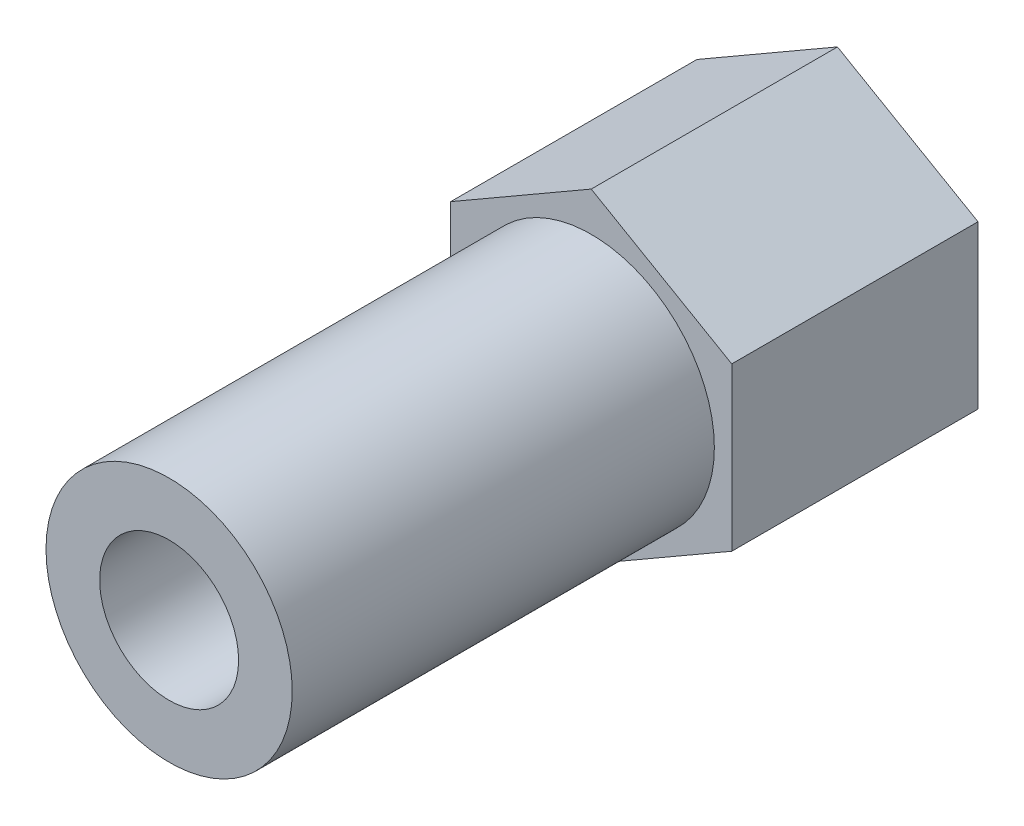
SolidWorks part; units mm, degrees
ref_plane "Plano frontal" through (0, 0, 0) normal (0, 0, 1) x (1, 0, 0)
ref_plane "Plano superior" through (0, 0, 0) normal (0, 1, 0) x (1, 0, 0)
ref_plane "Plano direito" through (0, 0, 0) normal (1, 0, 0) x (0, 0, -1)
sketch "Esboço1" plane through (0, 0, 0) normal (0, 0, 1) x (1, 0, 0)
  line L1 (0, 4.613) -> (-3.995, 2.3065)
  line L2 (-3.995, 2.3065) -> (-3.995, -2.3065)
  line L3 (-3.995, -2.3065) -> (0, -4.613)
  line L4 (0, -4.613) -> (3.995, -2.3065)
  line L5 (3.995, -2.3065) -> (3.995, 2.3065)
  line L6 (3.995, 2.3065) -> (0, 4.613)
  circle A0 centre (0, 0) radius 3.995 construction
  circle A1 centre (0, 0) radius 2
  dimension "D1" = 7.99
extrude "Ressalto-extrusão1" add sketch "Esboço1" along normal blind 7
sketch "Esboço2" plane through (0, 0, 7) normal (0, 0, 1) x (1, 0, 0)
  circle A0 centre (0, 0) radius 3.5
extrude "Ressalto-extrusão2" add sketch "Esboço2" along normal blind 12
sketch "Esboço3" plane through (0, 0, 19) normal (0, 0, 1) x (1, 0, 0)
  circle A0 centre (0, 0) radius 1.975
  dimension "D1" = 3.95
extrude "Corte-extrusão1" cut sketch "Esboço3" against normal blind 8
